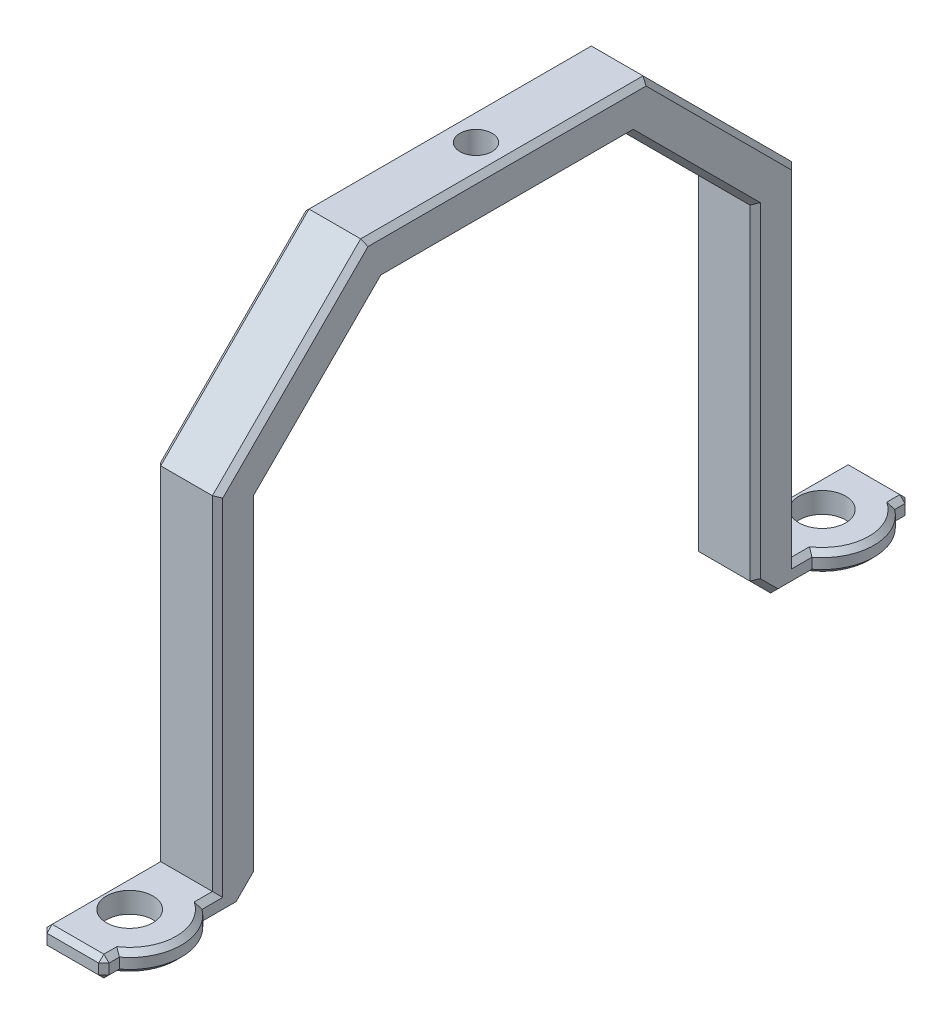
SolidWorks part; units mm, degrees
ref_plane "Front Plane" through (0, 0, 0) normal (0, 0, 1) x (1, 0, 0)
ref_plane "Top Plane" through (0, 0, 0) normal (0, 1, 0) x (1, 0, 0)
ref_plane "Right Plane" through (0, 0, 0) normal (1, 0, 0) x (0, 0, -1)
sketch "Sketch1" plane through (0, 0, 0) normal (0, 1, 0) x (1, 0, 0)
  line L1 (-3, -12) -> (3, -12)
  line L2 (-3, -12) -> (-3, 12)
  line L3 (-3, 12) -> (3, 12)
  line L4 (3, -12) -> (3, 12)
  circle A0 centre (0, 0) radius 1.55
  dimension "D1" = 3.1
  dimension "D2" = 3
  dimension "D3" = 3
  dimension "D4" = 12
  dimension "D5" = 12
extrude "Boss-Extrude1" add sketch "Sketch1" along normal blind 4
sketch "Sketch2" plane through (-3, 0, 0) normal (-1, 0, 0) x (0, 0, 1)
  line L0 (-12, 0) -> (-24, -12)
  line L1 (-24, -12) -> (-24, -43.5)
  line L2 (-24, -43.5) -> (-26, -45.5)
  line L3 (-26, -45.5) -> (-39, -45.5)
  line L4 (-39, -45.5) -> (-39, -43.5)
  line L6 (-28, -43.5) -> (-28, -10.3431)
  line L7 (-28, -10.3431) -> (-13.6569, 4)
  line L8 (-12, 0) -> (-12, 4)
  line L9 (-12, 4) -> (-13.6569, 4)
  line L10 (-39, -43.5) -> (-28, -43.5)
  line L11 (-12, 0) -> (12, 0) construction
  dimension "D1" = 4
  dimension "D2" = 4
  dimension "D3" = 12
  dimension "D4" = 2
  dimension "D5" = 2
  dimension "D6" = 2
  dimension "D7" = 45.5
  dimension "D8" = 11
extrude "Boss-Extrude2" add sketch "Sketch2" against normal up to surface (6 mm away) up to face at (3, 2, 0)
sketch "Sketch3" plane through (0, -43.5, 0) normal (0, 1, 0) x (1, 0, 0)
  line L0 (3, 39) -> (-3, 39) construction
  circle A0 centre (0, 33.5) radius 2.25
  dimension "D2" = 4.5
  dimension "D1" = 5.5
extrude "Cut-Extrude1" cut sketch "Sketch3" against normal through all
sketch "Sketch4" plane through (0, -43.5, 0) normal (0, 1, 0) x (1, 0, 0)
  line L0 (3, 29.5) -> (3, 37.5)
  line L1 (3, 39) -> (3, 28) construction
  arc A0 (3, 29.5) -> (3, 37.5) centre (0, 33.5) ccw
  arc A1 (3, 37.5) -> (3, 29.5) centre (0, 33.5) ccw construction
  dimension "D1" = 10
extrude "Boss-Extrude3" add sketch "Sketch4" against normal up to surface (2 mm away) up to face at (0, -45.5, -31.25)
mirror "Mirror1" about plane through (0, 0, 0) normal (0, 0, 1) of "Boss-Extrude3", "Boss-Extrude2", "Cut-Extrude1"
chamfer "Chamfer1" distance 0.5 angle 45 48 edges at (-3, 4, 0) (0, -45.5, -39) (0, -43.5, -39) (-3, -3.1716, -20.8284) (-3, -26.9216, -28) (-3, -43.5, -33.5) (-3, -44.5, -39) (-3, -45.5, -32.5) (-3, -44.5, -25) (-3, -27.75, -24) (-3, -6, -18) (3, -6, -18) (3, -27.75, -24) (3, -44.5, -25) (3, -45.5, -27.75) (3, -44.5, -39) (3, -43.5, -38.25) (3, -26.9216, -28) (3, -3.1716, -20.8284) (3, -43.5, -28.75) (3, -45.5, -38.25) (5, -43.5, -33.5) (5, -45.5, -33.5) (3, 4, 0) (-3, 0, 0) (3, -6, 18) (-3, -6, 18) (3, -27.75, 24) (-3, -27.75, 24) (3, -44.5, 25) (-3, -44.5, 25) (3, -45.5, 27.75) (0, -45.5, 39) (-3, -45.5, 32.5) (3, -44.5, 39) (0, -43.5, 39) (-3, -44.5, 39) (3, -43.5, 38.25) (-3, -43.5, 33.5) (3, -26.9216, 28) (-3, -26.9216, 28) (3, -3.1716, 20.8284) (-3, -3.1716, 20.8284) (3, 0, 0) (3, -43.5, 28.75) (3, -45.5, 38.25) (5, -43.5, 33.5) (5, -45.5, 33.5)
